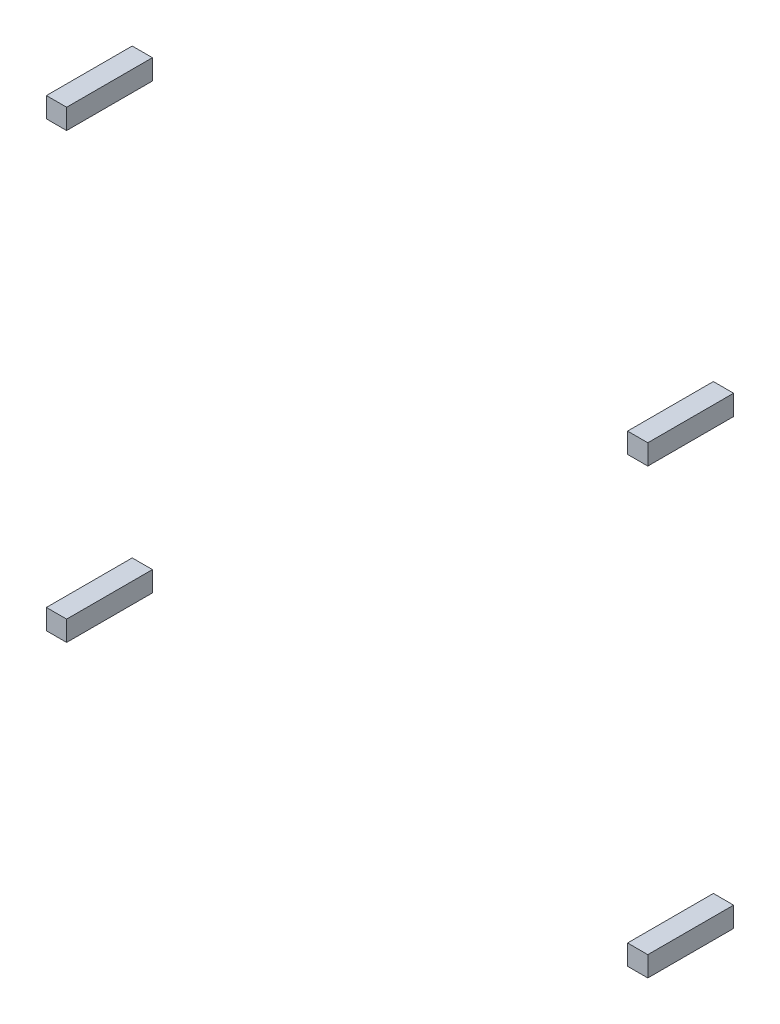
SolidWorks part; units mm, degrees
ref_plane "前视基准面" through (0, 0, 0) normal (0, 0, 1) x (1, 0, 0)
ref_plane "上视基准面" through (0, 0, 0) normal (0, 1, 0) x (1, 0, 0)
ref_plane "右视基准面" through (0, 0, 0) normal (1, 0, 0) x (0, 0, -1)
sketch "草图1" plane through (0, 0, 0) normal (0, 0, 1) x (1, 0, 0)
  line L0 (19.9664, 0.3536) -> (20.6736, 0.3536)
  line L1 (-0.3536, 0.3536) -> (0.3536, 0.3536)
  line L2 (-0.3536, 0.3536) -> (-0.3536, -0.3536)
  line L3 (-0.3536, -0.3536) -> (0.3536, -0.3536)
  line L4 (0.3536, 0.3536) -> (0.3536, -0.3536)
  line L5 (-0.3536, 0.3536) -> (0.3536, -0.3536) construction
  line L6 (-0.3536, -0.3536) -> (0.3536, 0.3536) construction
  line L7 (19.9664, 0.3536) -> (19.9664, -0.3536)
  line L8 (19.9664, -0.3536) -> (20.6736, -0.3536)
  line L9 (20.6736, 0.3536) -> (20.6736, -0.3536)
  line L10 (19.9664, 0.3536) -> (20.6736, -0.3536) construction
  line L11 (19.9664, -0.3536) -> (20.6736, 0.3536) construction
  line L12 (19.9664, 15.8536) -> (20.6736, 15.8536)
  line L13 (-0.3536, 15.8536) -> (0.3536, 15.8536)
  line L14 (-0.3536, 15.8536) -> (-0.3536, 15.1464)
  line L15 (-0.3536, 15.1464) -> (0.3536, 15.1464)
  line L16 (0.3536, 15.8536) -> (0.3536, 15.1464)
  line L17 (19.9664, 15.8536) -> (19.9664, 15.1464)
  line L18 (19.9664, 15.1464) -> (20.6736, 15.1464)
  line L19 (20.6736, 15.8536) -> (20.6736, 15.1464)
  line L20 (-0.3536, 15.8536) -> (0.3536, 15.1464) construction
  line L21 (-0.3536, 15.1464) -> (0.3536, 15.8536) construction
  line L22 (19.9664, 15.8536) -> (20.6736, 15.1464) construction
  line L23 (19.9664, 15.1464) -> (20.6736, 15.8536) construction
  circle A0 centre (0, 0) radius 0.5 construction
  circle A1 centre (20.32, 0) radius 0.5 construction
  circle A2 centre (0, 15.5) radius 0.5 construction
  circle A3 centre (20.32, 15.5) radius 0.5 construction
  dimension "D1" = 2
  dimension "D2" = 2
extrude "凸台-拉伸1" add sketch "草图1" along normal blind 3
